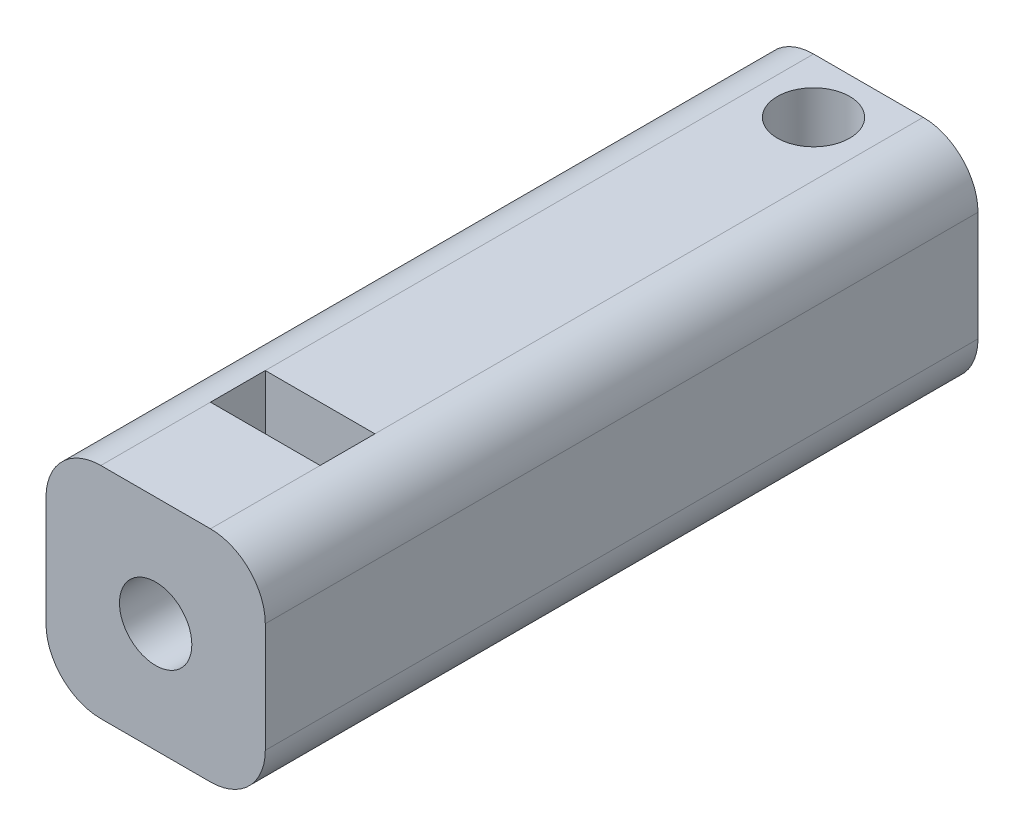
SolidWorks part; units mm, degrees
ref_plane "Plano frontal" through (0, 0, 0) normal (0, 0, 1) x (1, 0, 0)
ref_plane "Plano superior" through (0, 0, 0) normal (0, 1, 0) x (1, 0, 0)
ref_plane "Plano direito" through (0, 0, 0) normal (1, 0, 0) x (0, 0, -1)
sketch "Esboço2" plane through (0, 0, 0) normal (0, 0, 1) x (1, 0, 0)
  line L1 (-10, -10) -> (10, -10)
  line L2 (-10, -10) -> (-10, 10)
  line L3 (-10, 10) -> (10, 10)
  line L4 (10, -10) -> (10, 10)
  line L5 (-10, -10) -> (10, 10) construction
  line L6 (-10, 10) -> (10, -10) construction
  point P0 (0, 0)
  dimension "D1" = 20
  dimension "D2" = 20
extrude "Ressalto-extrusão1" add sketch "Esboço2" along normal blind 65
sketch "Esboço3" plane through (0, 0, 65) normal (0, 0, 1) x (1, 0, 0)
  circle A0 centre (0, 0) radius 3.3
  dimension "D1" = 6.6
extrude "Corte-extrusão1" cut sketch "Esboço3" against normal through all
sketch "Esboço4" plane through (0, -10, 0) normal (0, -1, 0) x (-1, 0, 0)
  line L0 (10, 0) -> (-10, 0) construction
  circle A0 centre (0, -5) radius 3.3
  dimension "D1" = 6.6
  dimension "D2" = 5
extrude "Corte-extrusão2" cut sketch "Esboço4" against normal through all
fillet "Filete1" radius 5 1 edges at (10, -10, 32.5)
fillet "Filete2" radius 5 1 edges at (10, 10, 32.5)
fillet "Filete3" radius 5 1 edges at (-10, 10, 32.5)
fillet "Filete4" radius 5 1 edges at (-10, -10, 32.5)
sketch "Esboço7" plane through (0, -10, 0) normal (0, -1, 0) x (-1, 0, 0)
  line L0 (5, -55) -> (-5, -55)
  line L1 (5, -65) -> (5, 0) construction
  line L2 (-5, 0) -> (-5, -65) construction
  line L3 (-5, -55) -> (-5, -50)
  line L4 (-5, -50) -> (5, -50)
  line L5 (5, -50) -> (5, -55)
  line L6 (5, -65) -> (-5, -65) construction
  dimension "D1" = 5
  dimension "D2" = 10
extrude "Corte-extrusão3" cut sketch "Esboço7" against normal through all
